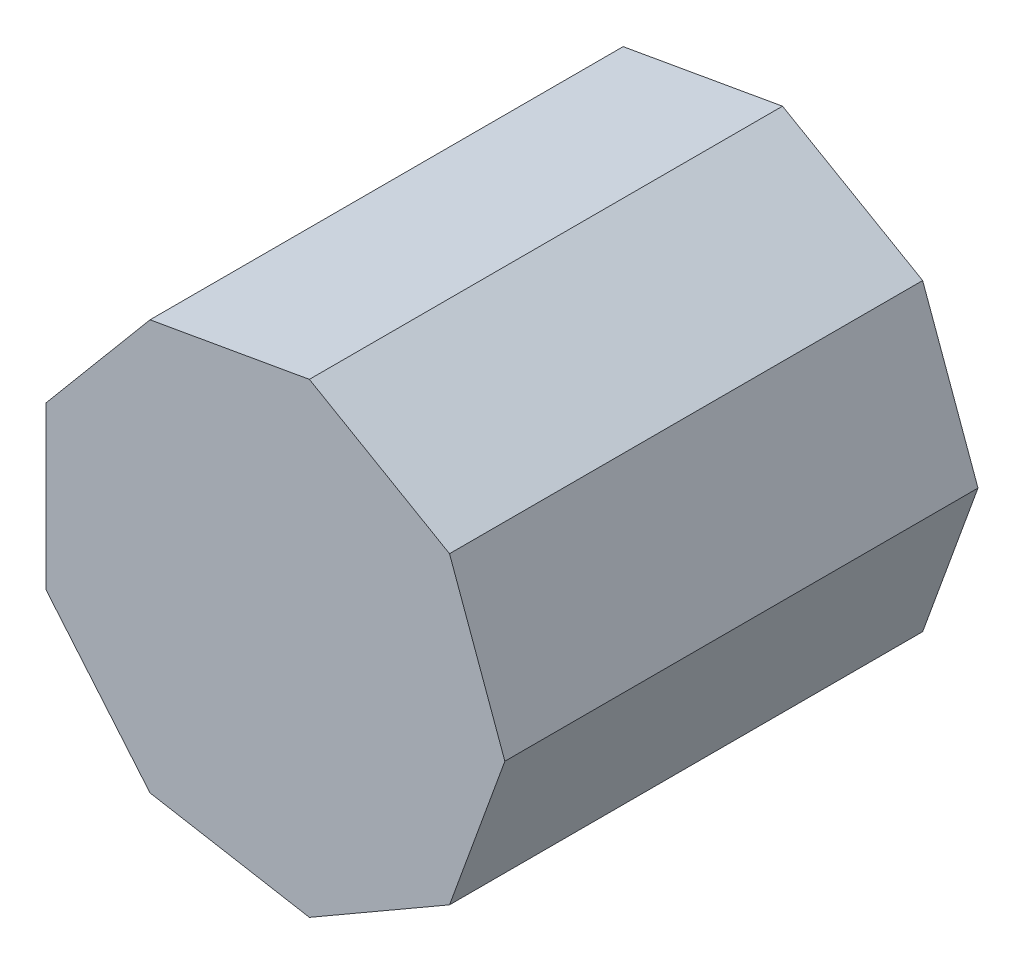
SolidWorks part; units mm, degrees
ref_plane "Front Plane" through (0, 0, 0) normal (0, 0, 1) x (1, 0, 0)
ref_plane "Top Plane" through (0, 0, 0) normal (0, 1, 0) x (1, 0, 0)
ref_plane "Right Plane" through (0, 0, 0) normal (1, 0, 0) x (0, 0, -1)
sketch "Sketch1" plane through (0, 0, 0) normal (0, 0, 1) x (1, 0, 0)
  line L0 (0, 0) -> (10, 0) construction
  line L1 (0, 0) -> (7.6604, 6.4279) construction
  line L2 (7.6604, 6.4279) -> (10, 0)
  line L3 (10, 0) -> (7.6604, -6.4279)
  line L4 (7.6604, -6.4279) -> (1.7365, -9.8481)
  line L5 (1.7365, -9.8481) -> (-5, -8.6603)
  line L6 (-5, -8.6603) -> (-9.3969, -3.4202)
  line L7 (-9.3969, -3.4202) -> (-9.3969, 3.4202)
  line L8 (-9.3969, 3.4202) -> (-5, 8.6603)
  line L9 (-5, 8.6603) -> (1.7365, 9.8481)
  line L10 (1.7365, 9.8481) -> (7.6604, 6.4279)
  circle A0 centre (0, 0) radius 10 construction
  point P23 (0, 0)
  dimension "D1" = 20
  dimension "D2" = 40
  dimension "D3" = 9
extrude "Boss-Extrude1" add sketch "Sketch1" along normal blind 20 contours L9 L10 L2 L3 L4 L5 L6 L7 L8
